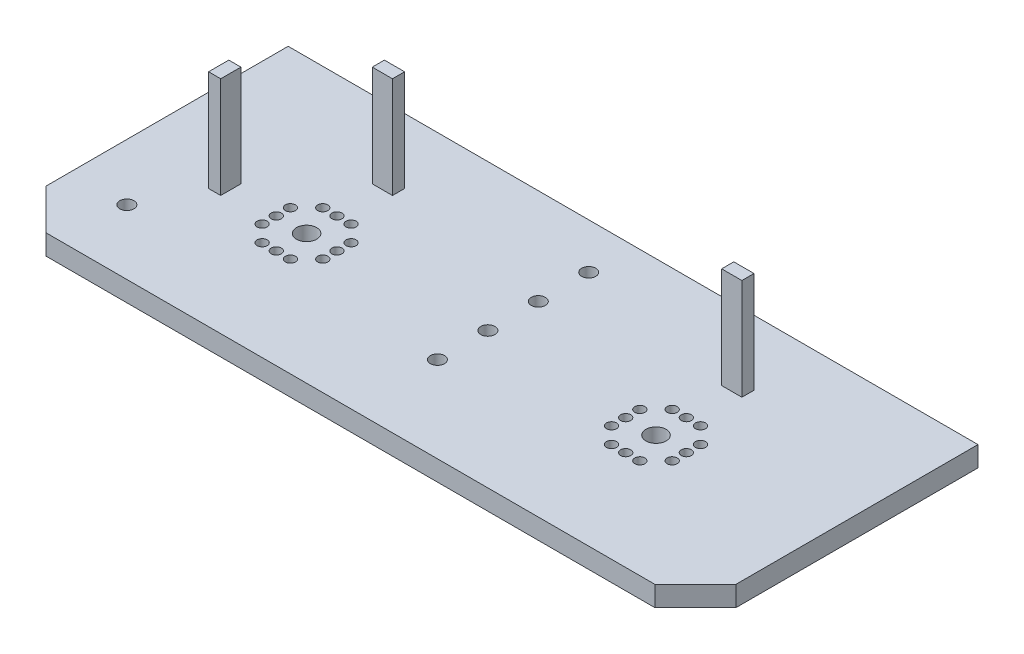
SolidWorks part; units mm, degrees
ref_plane "Front Plane" through (0, 0, 0) normal (0, 0, 1) x (1, 0, 0)
ref_plane "Top Plane" through (0, 0, 0) normal (0, 1, 0) x (1, 0, 0)
ref_plane "Right Plane" through (0, 0, 0) normal (1, 0, 0) x (0, 0, -1)
sketch "Sketch1" plane through (0, 0, 0) normal (0, 1, 0) x (1, 0, 0)
  line L0 (12.2307, -452.908) -> (12.2307, -522.788) construction
  line L1 (-73.0593, -452.908) -> (97.5207, -452.908)
  line L2 (-73.0593, -452.908) -> (-73.0593, -522.788)
  line L3 (-73.0593, -522.788) -> (97.5207, -522.788)
  line L4 (97.5207, -452.908) -> (97.5207, -522.788)
  point P6 (0, 0)
  point P7 (0, 0)
extrude "Boss-Extrude1" add sketch "Sketch1" along normal blind 5
sketch "Sketch6" plane through (0, 5, 0) normal (0, 1, 0) x (1, 0, 0)
  line L2 (-30.7043, -490.703) -> (-30.7043, -483.203) construction
  line L3 (-30.7043, -490.703) -> (-23.2043, -490.703) construction
  line L4 (-30.7043, -490.703) -> (-30.7043, -498.203) construction
  line L5 (-30.7043, -490.703) -> (-38.2043, -490.703) construction
  line L6 (-38.2043, -490.703) -> (-38.2043, -487.203) construction
  line L7 (-38.2043, -490.703) -> (-38.2043, -494.203) construction
  line L8 (-23.2043, -490.703) -> (-23.2043, -487.203) construction
  line L9 (-23.2043, -490.703) -> (-23.2043, -494.203) construction
  line L10 (-30.7043, -498.203) -> (-27.2043, -498.203) construction
  line L11 (-30.7043, -498.203) -> (-34.2043, -498.203) construction
  line L12 (-30.7043, -483.203) -> (-27.2043, -483.203) construction
  line L13 (-30.7043, -483.203) -> (-34.2043, -483.203) construction
  line L16 (55.6957, -490.703) -> (55.6957, -483.203) construction
  line L17 (55.6957, -490.703) -> (55.6957, -498.203) construction
  line L18 (55.6957, -490.703) -> (63.1957, -490.703) construction
  line L19 (55.6957, -490.703) -> (48.1957, -490.703) construction
  line L20 (55.6957, -483.203) -> (59.1957, -483.203) construction
  line L21 (55.6957, -483.203) -> (52.1957, -483.203) construction
  line L22 (48.1957, -490.703) -> (48.1957, -487.203) construction
  line L23 (48.1957, -490.703) -> (48.1957, -494.203) construction
  line L24 (55.6957, -498.203) -> (59.1957, -498.203) construction
  line L25 (55.6957, -498.203) -> (52.1957, -498.203) construction
  line L26 (63.1957, -490.703) -> (63.1957, -487.203) construction
  line L27 (63.1957, -490.703) -> (63.1957, -494.203) construction
  circle A0 centre (-30.7043, -483.203) radius 1.25
  circle A1 centre (-23.2043, -490.703) radius 1.25
  circle A2 centre (-30.7043, -498.203) radius 1.25
  circle A3 centre (-38.2043, -490.703) radius 1.25
  circle A4 centre (-38.2043, -487.203) radius 1.25
  circle A5 centre (-38.2043, -494.203) radius 1.25
  circle A6 centre (-23.2043, -487.203) radius 1.25
  circle A7 centre (-23.2043, -494.203) radius 1.25
  circle A8 centre (-27.2043, -498.203) radius 1.25
  circle A9 centre (-34.2043, -498.203) radius 1.25
  circle A10 centre (-27.2043, -483.203) radius 1.25
  circle A11 centre (-34.2043, -483.203) radius 1.25
  circle A12 centre (55.6957, -483.203) radius 1.25
  circle A13 centre (55.6957, -498.203) radius 1.25
  circle A14 centre (63.1957, -490.703) radius 1.25
  circle A15 centre (48.1957, -490.703) radius 1.25
  circle A16 centre (59.1957, -483.203) radius 1.25
  circle A17 centre (52.1957, -483.203) radius 1.25
  circle A18 centre (48.1957, -487.203) radius 1.25
  circle A19 centre (48.1957, -494.203) radius 1.25
  circle A20 centre (59.1957, -498.203) radius 1.25
  circle A21 centre (52.1957, -498.203) radius 1.25
  circle A22 centre (63.1957, -487.203) radius 1.25
  circle A23 centre (63.1957, -494.203) radius 1.25
extrude "Cut-Extrude2" cut sketch "Sketch6" against normal blind 8
sketch "Sketch7" plane through (0, 0, 0) normal (0, -1, 0) x (1, 0, 0)
  circle A0 centre (12.4957, 489.083) radius 1.75
  circle A1 centre (12.4957, 501.553) radius 1.75
extrude "Cut-Extrude3" cut sketch "Sketch7" against normal blind 8
sketch "Sketch8" plane through (0, 5, 0) normal (0, 1, 0) x (1, 0, 0)
  line L0 (55.6957, -471.968) -> (53.1957, -471.968)
  line L1 (97.5207, -452.908) -> (-73.0593, -452.908) construction
  line L2 (55.6957, -452.908) -> (55.6957, -471.968) construction
  line L3 (53.1957, -471.968) -> (58.1957, -471.968)
  line L4 (58.1957, -471.968) -> (58.1957, -468.968)
  line L5 (58.1957, -468.968) -> (53.1957, -468.968)
  line L6 (53.1957, -468.968) -> (53.1957, -471.968)
  line L7 (-30.7043, -483.203) -> (-30.7043, -452.908) construction
  line L8 (-30.7043, -452.908) -> (-30.7043, -471.968) construction
  line L9 (-30.7043, -468.968) -> (-33.2043, -468.968)
  line L10 (-30.7043, -468.968) -> (-28.2043, -468.968)
  line L11 (-28.2043, -468.968) -> (-28.2043, -471.968)
  line L12 (-28.2043, -471.968) -> (-33.2043, -471.968)
  line L13 (-33.2043, -471.968) -> (-33.2043, -468.968)
  line L14 (-38.2043, -490.703) -> (-49.4443, -490.703) construction
  line L15 (-49.4443, -490.703) -> (-49.4443, -493.203)
  line L16 (-49.4443, -493.203) -> (-49.4443, -488.203)
  line L17 (-49.4443, -488.203) -> (-52.4443, -488.203)
  line L18 (-52.4443, -488.203) -> (-52.4443, -493.203)
  line L19 (-52.4443, -493.203) -> (-49.4443, -493.203)
extrude "Boss-Extrude2" add sketch "Sketch8" along normal blind 25 contours L5 L6 L0 L3 L4 | L13 L12 L11 L10 L9 | L18 L19 L15 L16 L17
sketch "Sketch9" plane through (0, 5, 0) normal (0, 1, 0) x (1, 0, 0)
  line L0 (-59.0593, -506.788) -> (97.5207, -506.788) construction
  line L1 (97.5207, -522.788) -> (97.5207, -452.908) construction
  line L2 (97.5207, -506.788) -> (-60.9293, -506.788) construction
  line L4 (-60.9293, -506.788) -> (-59.0593, -506.788) construction
  circle A0 centre (12.4957, -476.613) radius 1.75
  circle A1 centre (12.4957, -464.143) radius 1.75
  circle A3 centre (-59.0593, -506.788) radius 1.75
  point P5 (0, 0)
extrude "Cut-Extrude4" cut sketch "Sketch9" against normal blind 10
sketch "Sketch10" plane through (0, 5, 0) normal (0, 1, 0) x (1, 0, 0)
  line L0 (-73.0593, -522.788) -> (-73.0593, -512.788)
  line L1 (-73.0593, -452.908) -> (-73.0593, -522.788) construction
  line L2 (-73.0593, -522.788) -> (-63.0593, -522.788)
  line L3 (-73.0593, -522.788) -> (97.5207, -522.788) construction
  line L4 (-63.0593, -522.788) -> (-73.0593, -512.788)
  line L5 (97.5207, -522.788) -> (87.5207, -522.788)
  line L6 (97.5207, -522.788) -> (97.5207, -512.788)
  line L7 (97.5207, -522.788) -> (97.5207, -452.908) construction
  line L8 (97.5207, -512.788) -> (87.5207, -522.788)
extrude "Cut-Extrude5" cut sketch "Sketch10" against normal blind 10
sketch "Sketch11" plane through (0, 5, 0) normal (0, 1, 0) x (1, 0, 0)
  line L0 (-38.2043, -490.703) -> (-23.2043, -490.703) construction
  line L1 (48.1957, -490.703) -> (63.1957, -490.703) construction
  circle A0 centre (-30.7043, -490.703) radius 2.5
  circle A1 centre (55.6957, -490.703) radius 2.5
extrude "Cut-Extrude6" cut sketch "Sketch11" against normal blind 10
